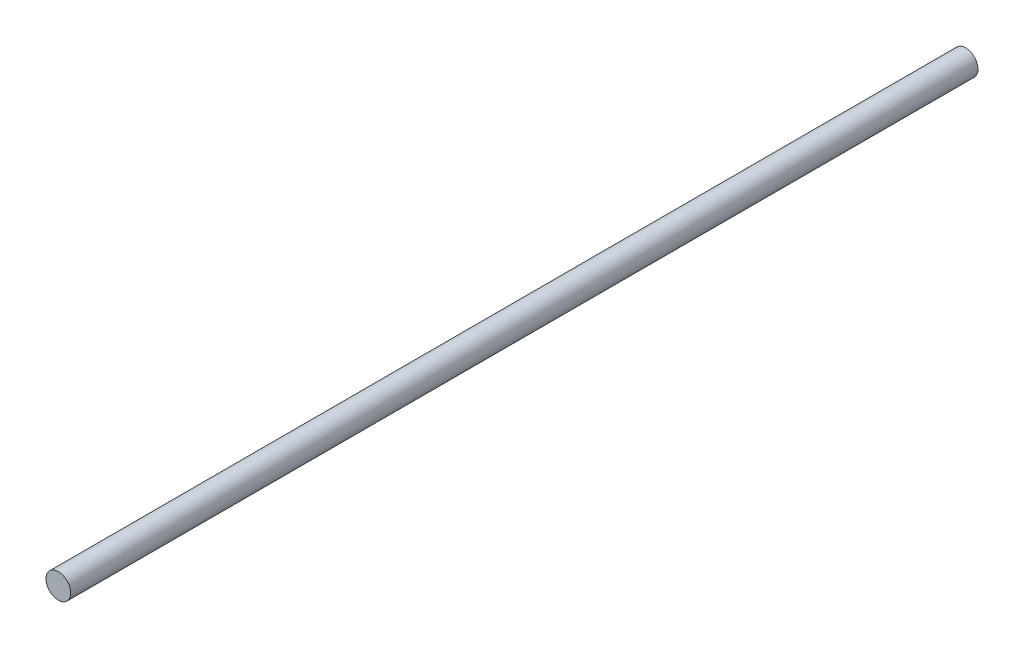
SolidWorks part; units mm, degrees
ref_plane "Alzado" through (0, 0, 0) normal (0, 0, 1) x (1, 0, 0)
ref_plane "Planta" through (0, 0, 0) normal (0, 1, 0) x (1, 0, 0)
ref_plane "Vista lateral" through (0, 0, 0) normal (1, 0, 0) x (0, 0, -1)
sketch "Croquis1" plane through (0, 0, 0) normal (0, 0, 1) x (1, 0, 0)
  circle A0 centre (0, 0) radius 1.5
  dimension "D1" = 3
extrude "Saliente-Extruir1" add sketch "Croquis1" against normal blind 110
